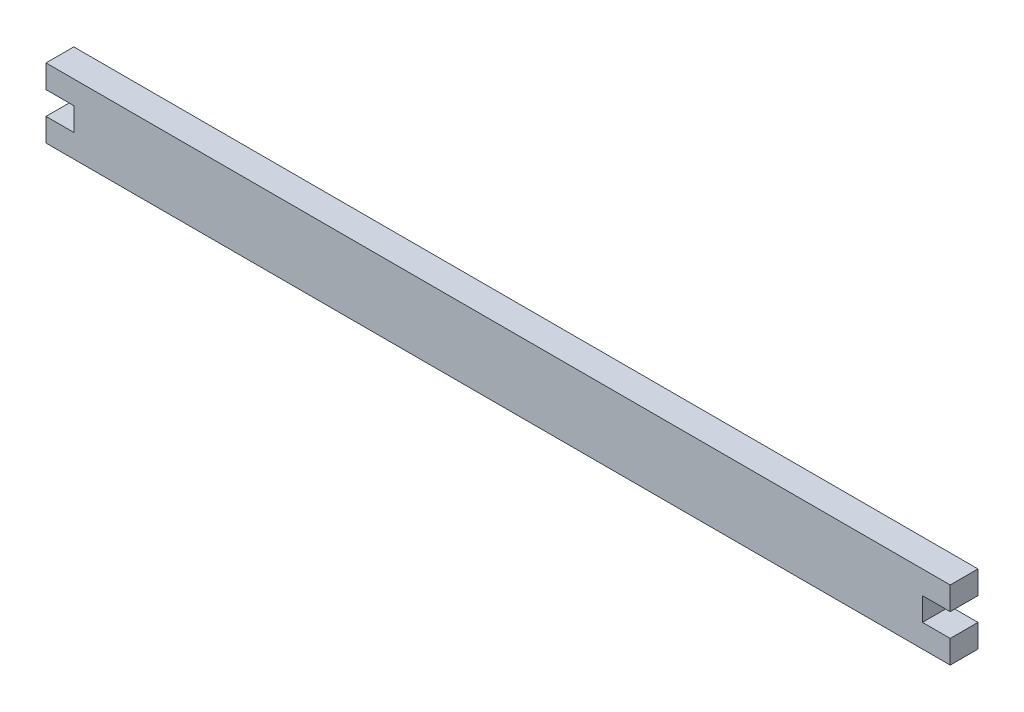
SolidWorks part; units mm, degrees
material "Teak"
ref_plane "Front Plane" through (0, 0, 0) normal (0, 0, 1) x (1, 0, 0)
ref_plane "Top Plane" through (0, 0, 0) normal (0, 1, 0) x (1, 0, 0)
ref_plane "Right Plane" through (0, 0, 0) normal (1, 0, 0) x (0, 0, -1)
sketch "Sketch1" plane through (0, 0, 0) normal (0, 0, 1) x (1, 0, 0)
  line L1 (-293, 22.5) -> (293, 22.5)
  line L2 (-293, 22.5) -> (-293, -22.5)
  line L3 (-293, -22.5) -> (293, -22.5)
  line L4 (293, 22.5) -> (293, -22.5)
  line L5 (-293, 22.5) -> (293, -22.5) construction
  line L6 (-293, -22.5) -> (293, 22.5) construction
  point P0 (0, 0)
  dimension "D1" = 586
  dimension "D2" = 45
extrude "Основа" add sketch "Sketch1" along normal blind 18
sketch "Sketch2" plane through (0, 0, 18) normal (0, 0, 1) x (1, 0, 0)
  line L0 (-293, -7.5) -> (-275, -7.5)
  line L1 (-293, 22.5) -> (-293, -22.5) construction
  line L2 (-275, -7.5) -> (-275, 7.5)
  line L3 (-275, 7.5) -> (-293, 7.5)
  line L4 (-293, 7.5) -> (-293, -7.5)
  line L5 (0, 22.5) -> (0, -22.5) construction
  line L6 (293, 22.5) -> (-293, 22.5) construction
  line L7 (-293, -22.5) -> (293, -22.5) construction
  point P13 (-293, 0)
  point P14 (-293, 0)
  dimension "D1" = 18
  dimension "D2" = 15
extrude "Шип" cut sketch "Sketch2" against normal up to next
sketch "Sketch3" plane through (0, 0, 18) normal (0, 0, 1) x (1, 0, 0)
  line L0 (-275, 7.5) -> (-293, 7.5) construction
  line L1 (-293, 22.5) -> (-293, 7.5) construction
  line L2 (-293, -7.5) -> (-293, -22.5) construction
  circle A0 centre (-284, 15) radius 1.75
  circle A1 centre (-284, -15) radius 1.75
  point P7 (-284, 7.5)
  point P12 (-293, 15)
  point P16 (-293, -15)
  dimension "D1" = 3.5
extrude "Крепежные" [suppressed] cut sketch "Sketch3" against normal up to next
mirror "Mirror1" about plane through (0, 0, 0) normal (1, 0, 0) of "Крепежные", "Шип"
